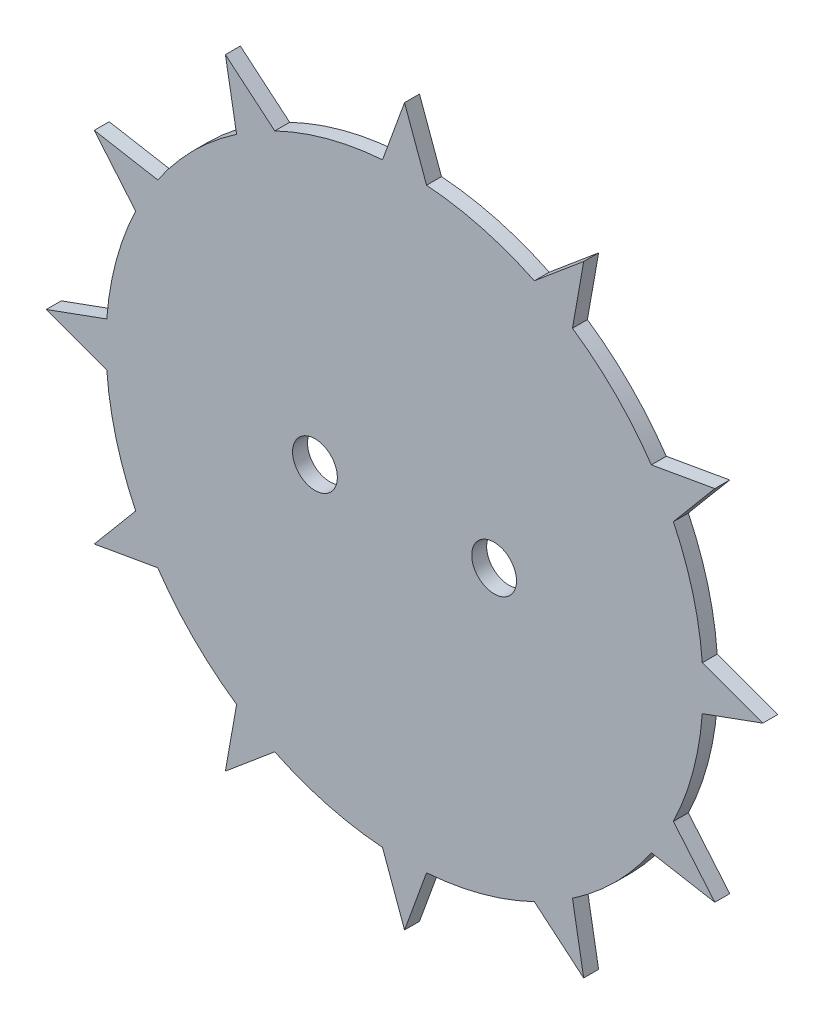
SolidWorks part; units mm, degrees
material "1023 Chapa de acero al carbono (SS)"
ref_plane "Alzado" through (0, 0, 0) normal (1, 0, 0) x (0, 1, 0)
ref_plane "Planta" through (0, 0, 0) normal (0, 0, 1) x (0, 1, 0)
ref_plane "Vista lateral" through (0, 0, 0) normal (0, 1, 0) x (-1, 0, 0)
sketch "Croquis1" plane through (0, 0, 0) normal (0, 0, 1) x (0, 1, 0)
  circle A0 centre (0, 0) radius 20
  dimension "D1" = 40
extrude "Saliente-Extruir1" add sketch "Croquis1" along normal blind 1
sketch "Croquis2" plane through (0, 0, 0) normal (0, 0, 1) x (0, 1, 0)
  line L0 (0, -20) -> (0, -24) construction
  line L1 (0, -24) -> (1.4757, -19.9455)
  line L2 (0, -24) -> (-1.4757, -19.9455)
  line L3 (-12, -20.7846) -> (-8.6947, -18.0112)
  line L4 (-12, -20.7846) -> (-11.2508, -16.5354)
  line L5 (-20.7846, -12) -> (-16.5354, -11.2508)
  line L6 (-20.7846, -12) -> (-18.0112, -8.6947)
  line L7 (-24, 0) -> (-19.9455, -1.4757)
  line L8 (-24, 0) -> (-19.9455, 1.4757)
  line L9 (-20.7846, 12) -> (-18.0112, 8.6947)
  line L10 (-20.7846, 12) -> (-16.5354, 11.2508)
  line L11 (-12, 20.7846) -> (-11.2508, 16.5354)
  line L12 (-12, 20.7846) -> (-8.6947, 18.0112)
  line L13 (0, 24) -> (-1.4757, 19.9455)
  line L14 (0, 24) -> (1.4757, 19.9455)
  line L15 (12, 20.7846) -> (8.6947, 18.0112)
  line L16 (12, 20.7846) -> (11.2508, 16.5354)
  line L17 (20.7846, 12) -> (16.5354, 11.2508)
  line L18 (20.7846, 12) -> (18.0112, 8.6947)
  line L19 (24, 0) -> (19.9455, 1.4757)
  line L20 (24, 0) -> (19.9455, -1.4757)
  line L21 (20.7846, -12) -> (18.0112, -8.6947)
  line L22 (20.7846, -12) -> (16.5354, -11.2508)
  line L23 (12, -20.7846) -> (11.2508, -16.5354)
  line L24 (12, -20.7846) -> (8.6947, -18.0112)
  circle A0 centre (0, 0) radius 20 construction
  arc A1 (-1.4757, -19.9455) -> (1.4757, -19.9455) centre (0, 0) ccw
  arc A2 (-11.2508, -16.5354) -> (-8.6947, -18.0112) centre (0, 0) ccw
  arc A3 (-18.0112, -8.6947) -> (-16.5354, -11.2508) centre (0, 0) ccw
  arc A4 (-19.9455, 1.4757) -> (-19.9455, -1.4757) centre (0, 0) ccw
  arc A5 (-16.5354, 11.2508) -> (-18.0112, 8.6947) centre (0, 0) ccw
  arc A6 (-8.6947, 18.0112) -> (-11.2508, 16.5354) centre (0, 0) ccw
  arc A7 (1.4757, 19.9455) -> (-1.4757, 19.9455) centre (0, 0) ccw
  arc A8 (11.2508, 16.5354) -> (8.6947, 18.0112) centre (0, 0) ccw
  arc A9 (18.0112, 8.6947) -> (16.5354, 11.2508) centre (0, 0) ccw
  arc A10 (19.9455, -1.4757) -> (19.9455, 1.4757) centre (0, 0) ccw
  arc A11 (16.5354, -11.2508) -> (18.0112, -8.6947) centre (0, 0) ccw
  arc A12 (8.6947, -18.0112) -> (11.2508, -16.5354) centre (0, 0) ccw
  point P45 (0, 0)
  dimension "D1" = 4
  dimension "D2" = 20
  dimension "D3" = 12
extrude "Saliente-Extruir2" add sketch "Croquis2" along normal blind 1
sketch "Croquis3" plane through (0, 0, 1) normal (0, 0, 1) x (1, 0, 0)
  line L0 (-27.0114, -20) -> (27.0114, -20)
  circle A0 centre (0, 0) radius 20 construction
  point P6 (0, -20)
  dimension "D1" = 40
sketch "Croquis4" plane through (0, 0, 1) normal (0, 0, 1) x (1, 0, 0)
  line L0 (0, 0) -> (0, -9.6128) construction
  circle A0 centre (6, 0) radius 1.5
  circle A1 centre (-6, 0) radius 1.5
  dimension "D1" = 3
  dimension "D2" = 6
extrude "Cortar-Extruir1" cut sketch "Croquis4" against normal up to next
